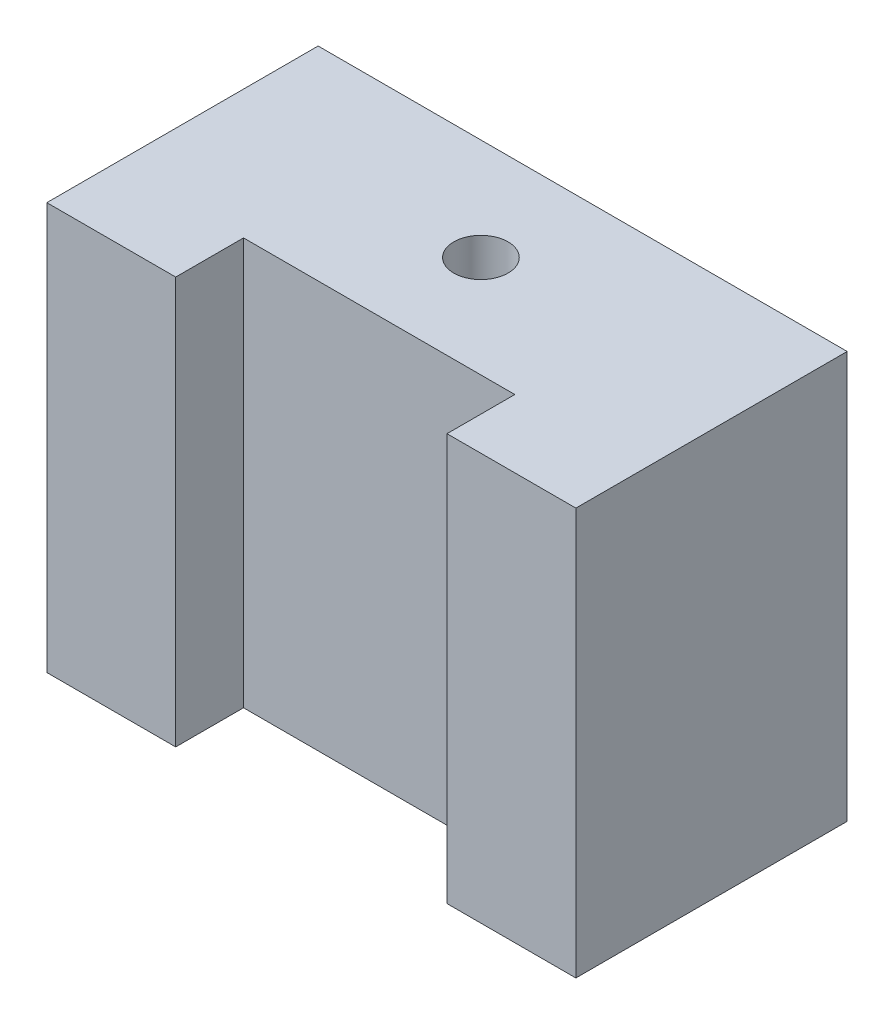
SolidWorks part; units mm, degrees
ref_plane "前视基准面" through (0, 0, 0) normal (0, 0, 1) x (1, 0, 0)
ref_plane "上视基准面" through (0, 0, 0) normal (0, 1, 0) x (1, 0, 0)
ref_plane "右视基准面" through (0, 0, 0) normal (1, 0, 0) x (0, 0, -1)
sketch "草图1" plane through (0, 0, 0) normal (0, 0, 1) x (1, 0, 0)
  line L1 (-39, -30) -> (39, -30)
  line L2 (-39, -30) -> (-39, 30)
  line L3 (-39, 30) -> (39, 30)
  line L4 (39, -30) -> (39, 30)
  line L5 (-39, -30) -> (39, 30) construction
  line L6 (-39, 30) -> (39, -30) construction
  point P0 (0, 0)
  dimension "D1" = 60
  dimension "D2" = 78
extrude "凸台-拉伸1" add sketch "草图1" along normal blind 30
sketch "草图2" plane through (0, 0, 30) normal (0, 0, 1) x (1, 0, 0)
  line L0 (39, 30) -> (-39, 30) construction
  line L1 (-20, -30) -> (20, -30)
  line L2 (-20, -30) -> (-20, 30)
  line L3 (-20, 30) -> (20, 30)
  line L4 (20, -30) -> (20, 30)
  line L5 (-20, -30) -> (20, 30) construction
  line L6 (-20, 30) -> (20, -30) construction
  line L8 (-39, -30) -> (39, -30)
  line L9 (-39, -30) -> (-39, 30)
  line L10 (-39, 30) -> (39, 30)
  line L11 (39, -30) -> (39, 30)
  line L12 (-39, -30) -> (39, 30) construction
  line L13 (-39, 30) -> (39, -30) construction
  point P0 (0, 0)
  point P8 (0, 0)
  line M2 (39, -30) -> (39, 30)
  line M3 (39, 30) -> (-39, 30)
  line M4 (-39, 30) -> (-39, -30)
  line M5 (-39, -30) -> (39, -30)
  dimension "D1" = 40
extrude "凸台-拉伸2" add sketch "草图2" along normal blind 10 contours L4 M5 M2 M3 | L2 M5 M3 M4
sketch "草图3" plane through (0, 30, 0) normal (0, 1, 0) x (1, 0, 0)
  line L0 (39, 0) -> (-39, 0) construction
  circle A0 centre (0, -15) radius 4
  dimension "D1" = 8
  dimension "D2" = 15
extrude "切除-拉伸1" cut sketch "草图3" against normal blind 60
